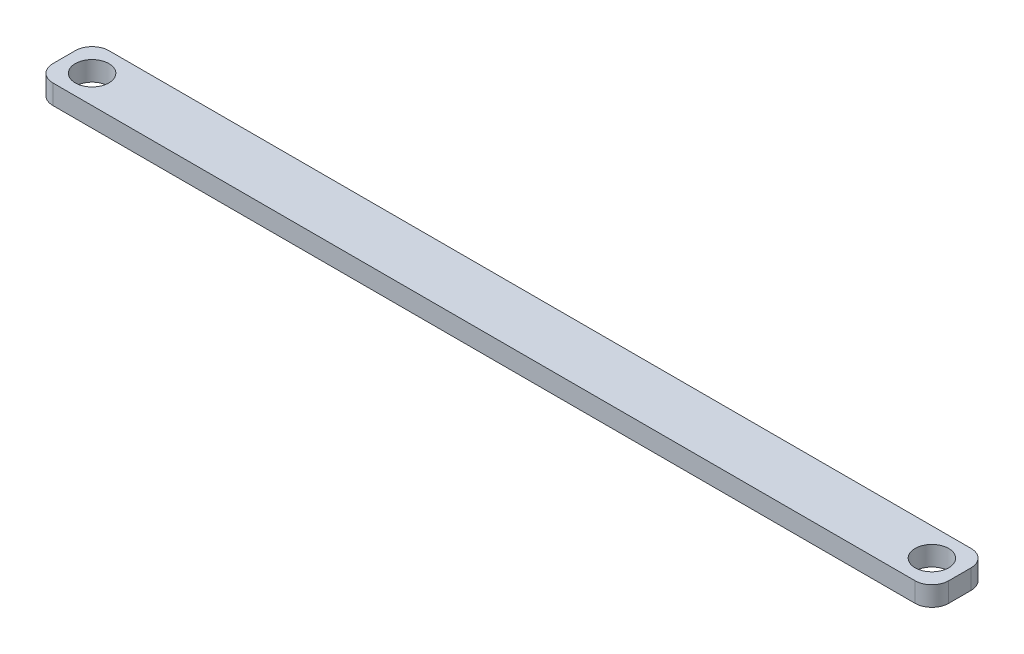
SolidWorks part; units mm, degrees
ref_plane "Front Plane" through (0, 0, 0) normal (0, 0, 1) x (1, 0, 0)
ref_plane "Top Plane" through (0, 0, 0) normal (0, 1, 0) x (1, 0, 0)
ref_plane "Right Plane" through (0, 0, 0) normal (1, 0, 0) x (0, 0, -1)
sketch "Sketch1" plane through (0, 0, 0) normal (0, 1, 0) x (1, 0, 0)
  line L1 (3, 0) -> (157, 0)
  line L2 (0, -3) -> (0, -7)
  line L3 (3, -10) -> (157, -10)
  line L4 (160, -3) -> (160, -7)
  circle A0 centre (5, -5) radius 3
  circle A1 centre (155, -5) radius 3
  arc A2 (157, -10) -> (160, -7) centre (157, -7) ccw
  arc A3 (157, 0) -> (160, -3) centre (157, -3) cw
  arc A4 (0, -7) -> (3, -10) centre (3, -7) ccw
  arc A5 (3, 0) -> (0, -3) centre (3, -3) ccw
  point P11 (160, -10)
  point P14 (160, 0)
  point P17 (0, -10)
  point P20 (0, 0)
  dimension "D3" = 5
  dimension "D4" = 150
  dimension "D5" = 6
  dimension "D6" = 6
  dimension "D7" = 3
  dimension "D1" = 10
  dimension "D2" = 160
extrude "Boss-Extrude1" add sketch "Sketch1" along normal blind 3.5
